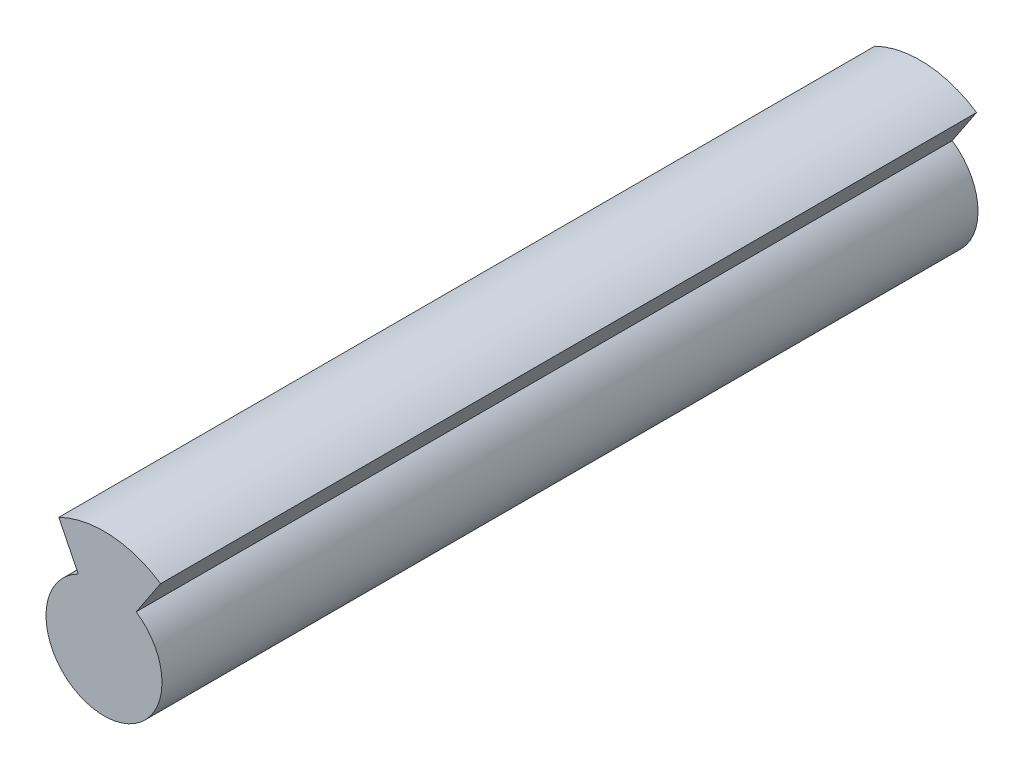
SolidWorks part; units mm, degrees
ref_plane "Front Plane" through (0, 0, 0) normal (0, 0, 1) x (1, 0, 0)
ref_plane "Top Plane" through (0, 0, 0) normal (0, 1, 0) x (1, 0, 0)
ref_plane "Right Plane" through (0, 0, 0) normal (1, 0, 0) x (0, 0, -1)
sketch "Sketch1" plane through (0, 0, 0) normal (0, 0, 1) x (1, 0, 0)
  line L0 (-6.6467, 13.447) -> (0, 0)
  line L1 (0, 0) -> (8.3221, 12.4797)
  circle A0 centre (0, 0) radius 8.53
  arc A2 (-6.6467, 13.447) -> (8.3221, 12.4797) centre (0, 0) cw
  dimension "D1" = 17.06
  dimension "D2" = 15
  dimension "D3" = 60
extrude "Boss-Extrude1" add sketch "Sketch1" along normal blind 120 contours A2 L0 A0 L1 | L0 A0 L1 | L1 A0 L0
equation "\"D1@Sketch1\"=8.53*2"
